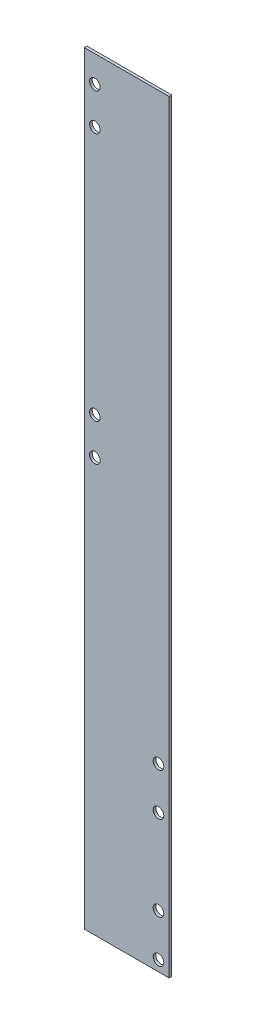
SolidWorks part; units mm, degrees
ref_plane "Front Plane" through (0, 0, 0) normal (0, 0, 1) x (1, 0, 0)
ref_plane "Top Plane" through (0, 0, 0) normal (0, 1, 0) x (1, 0, 0)
ref_plane "Right Plane" through (0, 0, 0) normal (1, 0, 0) x (0, 0, -1)
sketch "Sketch1" plane through (0, 0, 0) normal (1, 0, 0) x (0, 0, -1)
  line L0 (0, 0) -> (0, -914.4)
  line L1 (0, -914.4) -> (3.175, -914.4)
  line L4 (3.175, -914.4) -> (3.175, 0)
  line L5 (3.175, 0) -> (0, 0)
  dimension "D1" = 914.4
  dimension "D2" = 3.175
extrude "Extrude1" add sketch "Sketch1" along normal blind 101.6
sketch "Sketch3" plane through (0, 0, 0) normal (0, 0, 1) x (1, 0, 0)
  line L0 (101.6, 0) -> (101.6, -914.4) construction
  line L1 (101.6, -914.4) -> (0, -914.4) construction
  circle A0 centre (88.9, -901.7) radius 6.35
  circle A1 centre (88.9, -850.9) radius 6.35
  circle A2 centre (88.9, -749.3) radius 6.35
  circle A3 centre (88.9, -698.5) radius 6.35
  dimension "D1" = 12.7
  dimension "D2" = 50.8
  dimension "D3" = 101.6
  dimension "D4" = 50.8
  dimension "D5" = 12.7
  dimension "D6" = 12.7
extrude "Cut-Extrude2" cut sketch "Sketch3" against normal blind 50.8
sketch "Sketch4" plane through (0, 0, 0) normal (0, 0, 1) x (1, 0, 0)
  line L0 (0, 0) -> (0, -914.4) construction
  circle A0 centre (12.7, -419.1) radius 6.35
  circle A1 centre (12.7, -374.65) radius 6.35
  circle A2 centre (12.7, -76.2) radius 6.35
  circle A3 centre (12.7, -31.75) radius 6.35
  circle A4 centre (88.9, -698.5) radius 6.35 construction
  dimension "D1" = 12.7
  dimension "D2" = 44.45
  dimension "D3" = 298.45
  dimension "D4" = 44.45
  dimension "D5" = 279.4
  dimension "D6" = 12.7
extrude "Cut-Extrude3" cut sketch "Sketch4" against normal blind 50.8
